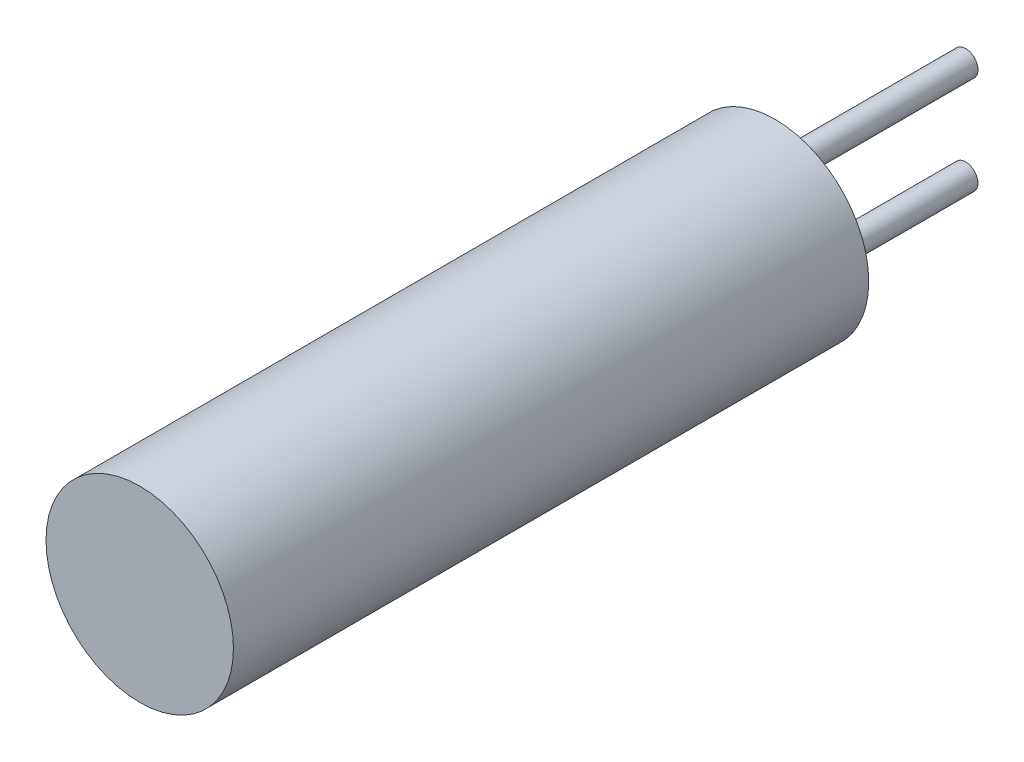
SolidWorks part; units mm, degrees
ref_plane "Alzado" through (0, 0, 0) normal (0, 0, 1) x (1, 0, 0)
ref_plane "Planta" through (0, 0, 0) normal (0, 1, 0) x (1, 0, 0)
ref_plane "Vista lateral" through (0, 0, 0) normal (1, 0, 0) x (0, 0, -1)
sketch "Croquis4" plane through (0, 0, 0) normal (0, 0, 1) x (1, 0, 0)
  circle A0 centre (0, 0) radius 2.95
sketch "Croquis5" plane through (0, 0, 0) normal (0, 0, 1) x (1, 0, 0)
  circle A0 centre (0, 1.4898) radius 0.3898
  circle A1 centre (0, -1.6023) radius 0.3898
extrude "Saliente-Extruir3" add sketch "Croquis5" against normal blind 6
extrude "Saliente-Extruir4" add sketch "Croquis4" along normal blind 20
